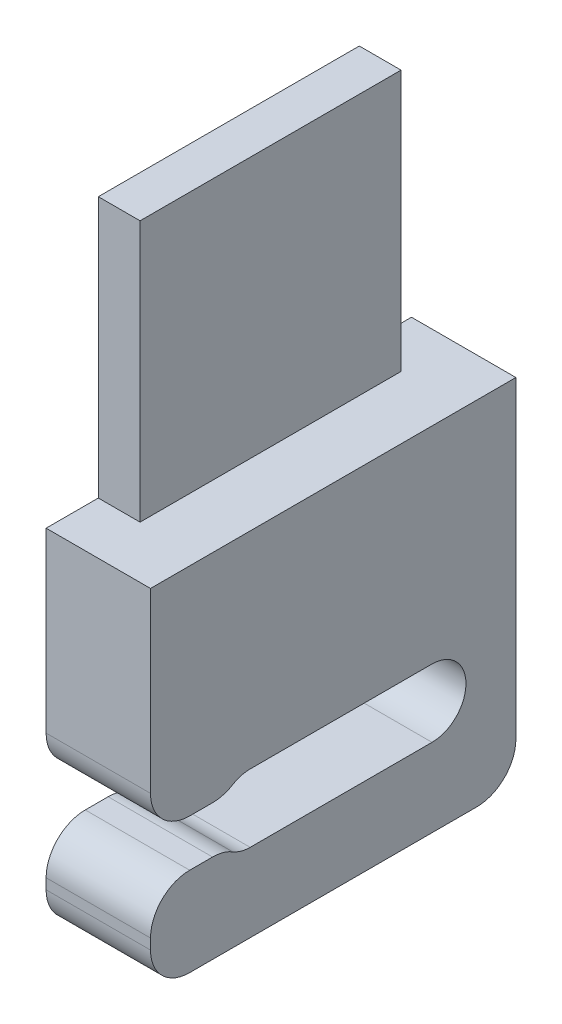
SolidWorks part; units mm, degrees
ref_plane "Front Plane" through (0, 0, 0) normal (0, 0, 1) x (1, 0, 0)
ref_plane "Top Plane" through (0, 0, 0) normal (0, 1, 0) x (1, 0, 0)
ref_plane "Right Plane" through (0, 0, 0) normal (1, 0, 0) x (0, 0, -1)
sketch "Sketch1" plane through (0, 0, 0) normal (1, 0, 0) x (0, 0, -1)
  line L1 (0, 0) -> (10, 0)
  line L2 (0, 0) -> (0, -10)
  line L3 (0, -10) -> (10, -10)
  line L4 (10, 0) -> (10, -10)
  dimension "D1" = 10
  dimension "D2" = 10
extrude "Boss-Extrude1" add sketch "Sketch1" along normal blind 1.6
sketch "Sketch2" plane through (0, 0, 0) normal (0, 0, 1) x (1, 0, 0)
  line L3 (1.2, -12) -> (0, -12)
  line L4 (0, -10) -> (0, -12)
  line L5 (1.6, -10) -> (4, -10)
  line L7 (2.8, -12) -> (4, -12)
  line L8 (4, -10) -> (4, -12)
  line L9 (1.2, -12) -> (2.8, -12)
  line L11 (0, -10) -> (1.6, -10)
  point P10 (0, 0)
  line M8 (0, -10) -> (1.6, -10)
  dimension "D1" = 4
  dimension "D2" = 2
  dimension "D3" = 0
extrude "Boss-Extrude2" add sketch "Sketch2" against normal up to surface (10 mm away) contours L3 L9 L7 L8 L5 L4 M8 up to face at (0.8, -5, -10)
sketch "Sketch3" plane through (0, 0, 0) normal (0, 0, 1) x (1, 0, 0)
  line L9 (4, -10) -> (0, -10)
  line L10 (4, -10) -> (4, -12)
  line L11 (4, -12) -> (0, -12)
  line L12 (0, -10) -> (0, -12)
extrude "Boss-Extrude3" add sketch "Sketch3" along normal blind 2
sketch "Sketch4" plane through (0, 0, -10) normal (0, 0, -1) x (-1, 0, 0)
  line L0 (-4, -10) -> (-1.6, -10) construction
  line L5 (-4, -10) -> (0, -10)
  line L6 (-4, -10) -> (-4, -12)
  line L7 (-4, -12) -> (0, -12)
  line L8 (0, -10) -> (0, -12)
  line L9 (-4, -12) -> (-4, -10) construction
  line L10 (0, -12) -> (-4, -12) construction
  line L11 (0, -12) -> (0, 0) construction
extrude "Boss-Extrude4" add sketch "Sketch4" along normal blind 2
sketch "Sketch5" plane through (4, 0, 0) normal (1, 0, 0) x (0, 0, -1)
  line L0 (12, -10) -> (12, -12) construction
  line L1 (-2, -12) -> (12, -12)
  line L2 (-2, -12) -> (-2, -22)
  line L3 (-0.5, -23.5) -> (10.5, -23.5)
  line L4 (12, -12) -> (12, -22)
  line L6 (8.7871, -17.9) -> (1.8187, -17.9)
  line L8 (8.7871, -20.5) -> (1.8187, -20.5)
  line L11 (1.8187, -18.3) -> (-2, -18.3)
  line L12 (-2, -16.6655) -> (-2, -18.3)
  line L15 (1.8187, -20.1) -> (-2, -20.1)
  line L16 (-2, -16.6655) -> (-2, -20.1)
  circle A0 centre (8.7871, -19.2) radius 1.3
  circle A1 centre (1.8187, -19.2) radius 1.3
  arc A2 (10.5, -23.5) -> (12, -22) centre (10.5, -22) ccw
  arc A3 (-2, -22) -> (-0.5, -23.5) centre (-0.5, -22) ccw
  point P22 (12, -23.5)
  line M5 (-2, -12) -> (12, -12)
  dimension "D2" = 2.6
  dimension "D3" = 2.6
  dimension "D7" = 1.5
  dimension "D1" = 11.5
  dimension "D4" = 0.9
  dimension "D5" = 0.9
  dimension "D6" = 4.3
extrude "Boss-Extrude5" add sketch "Sketch5" against normal up to surface (4 mm away) contours L2 A3 L3 A2 L4 L11 A1 L6 A0 L8 L15 M5 up to face at (0, -8, -5)
fillet "Fillet1" radius 1.5 4 edges at (2, -20.1, 2) (2, -20.1, -0.8807) (2, -18.3, -0.8807) (2, -18.3, 2)
